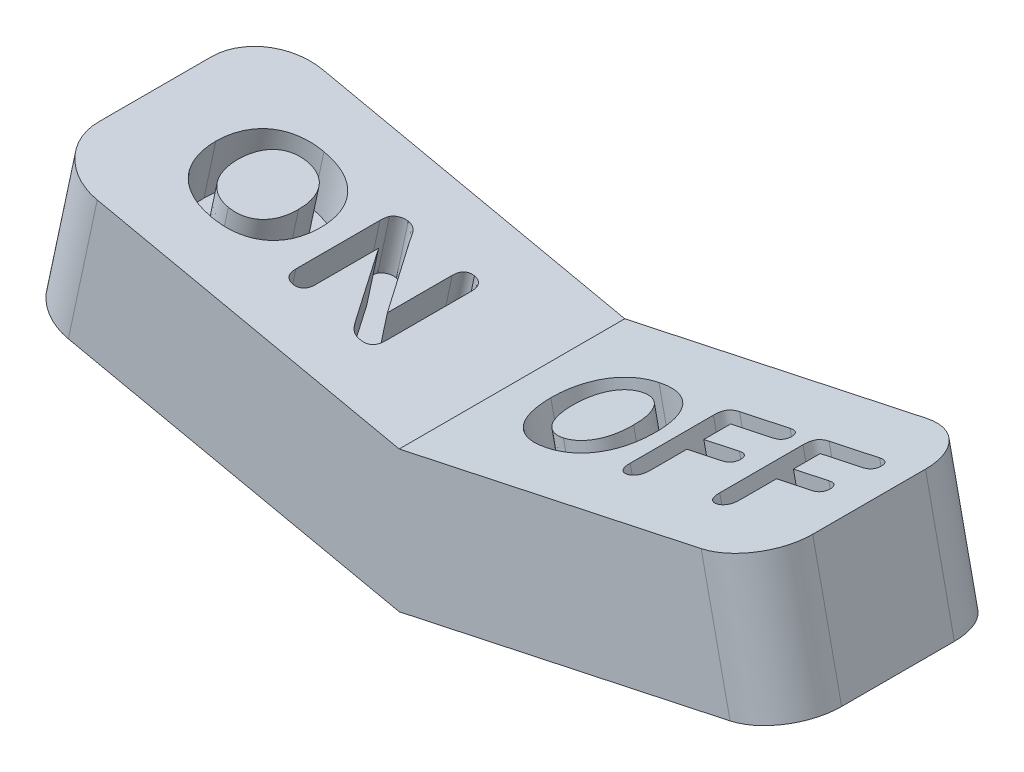
SolidWorks part; units mm, degrees
material "PVC hart"
ref_plane "Ebene vorne" through (0, 0, 0) normal (0, 0, 1) x (1, 0, 0)
ref_plane "Ebene oben" through (0, 0, 0) normal (0, 1, 0) x (1, 0, 0)
ref_plane "Ebene rechts" through (0, 0, 0) normal (1, 0, 0) x (0, 0, -1)
sketch "Skizze1" plane through (0, 0, 0) normal (0, 0, 1) x (1, 0, 0)
  line L5 (0.6676, 3.8569) -> (7, 2.5)
  line L6 (7, 2.5) -> (13.3324, 3.8569)
  line L9 (7, 0) -> (0.1554, 1.4667)
  line L10 (7, 0) -> (13.8446, 1.4667)
  line L11 (0.1554, 1.4667) -> (0.6676, 3.8569)
  line L12 (13.8446, 1.4667) -> (13.3324, 3.8569)
  point P0 (0, 0)
  dimension "D2" = 7
  dimension "D4" = 7
extrude "Aufsatz-Linear austragen2" add sketch "Skizze1" along normal blind 4
sketch "Skizze2" plane through (0.8195, 3.8244, 0) normal (0.2095, 0.9778, 0) x (0.9778, -0.2095, 0)
  line L0 (6.3208, -4) -> (-0.1554, -4) construction
  line L1 (-0.1554, -4) -> (-0.1554, 0) construction
  text T0 "ON" font "Arial Rounded MT Bold" height 2
  dimension "D1" = 1
  dimension "D2" = 1
extrude "Schnitt-Linear austragen1" cut sketch "Skizze2" against normal blind 1
sketch "Skizze3" plane through (-0.2049, 0.9561, 0) normal (-0.2095, 0.9778, 0) x (0.9778, 0.2095, 0)
  line L0 (13.8446, -4) -> (7.3684, -4) construction
  line L1 (7.3684, -4) -> (7.3684, 0) construction
  text T0 "OFF" font "Arial Rounded MT Bold" height 2
  dimension "D1" = 1
  dimension "D2" = 0.6
extrude "Schnitt-Linear austragen2" cut sketch "Skizze3" against normal blind 1
sketch "Skizze4" plane through (0.61, 2.8466, 0) normal (0.2095, 0.9778, 0) x (0.9778, -0.2095, 0)
fillet "Verrundung1" radius 1 4 edges at (13.5885, 2.6618, 0) (13.5885, 2.6618, 4) (0.4115, 2.6618, 0) (0.4115, 2.6618, 4)
